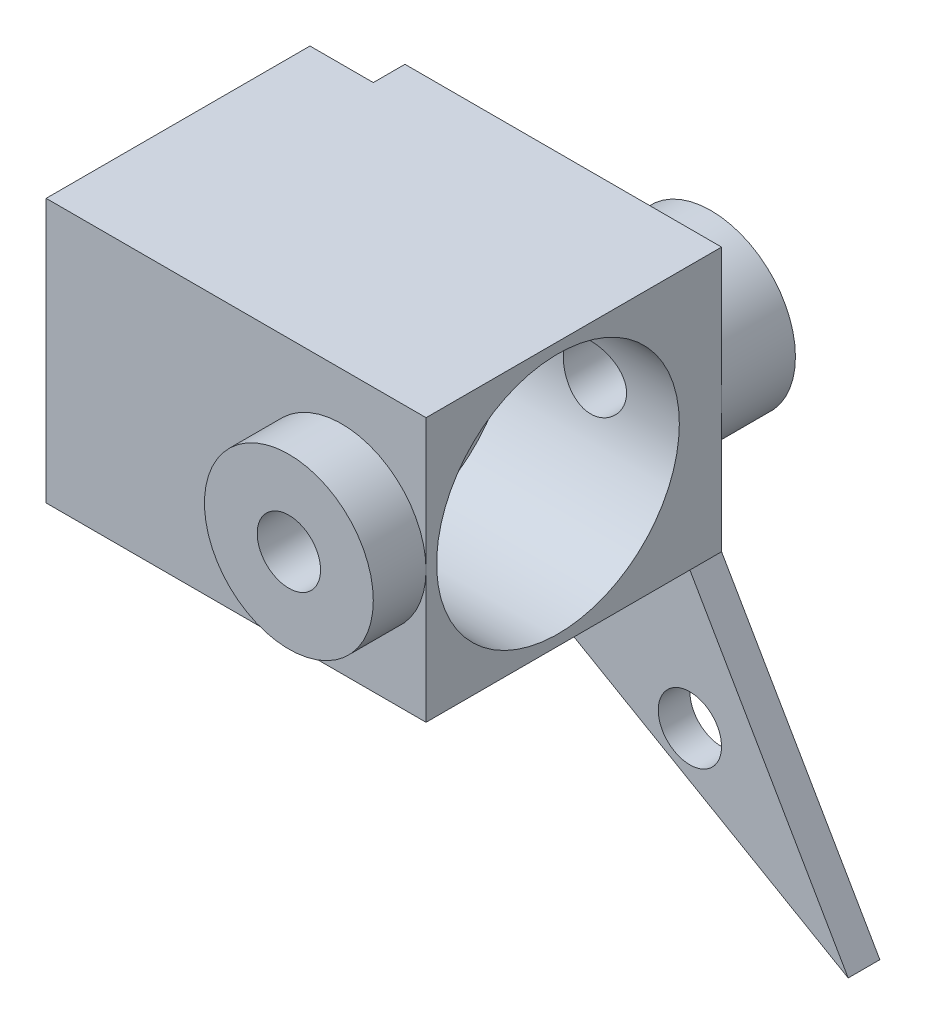
SolidWorks part; units mm, degrees
ref_plane "前视基准面" through (0, 0, 0) normal (0, 0, 1) x (1, 0, 0)
ref_plane "上视基准面" through (0, 0, 0) normal (0, 1, 0) x (1, 0, 0)
ref_plane "右视基准面" through (0, 0, 0) normal (1, 0, 0) x (0, 0, -1)
other "Configuration Table"
sketch "草图1" plane through (0, 0, 0) normal (0, 0, 1) x (1, 0, 0)
  line L0 (-52.6872, 0) -> (52.6872, 0) construction
  line L1 (0, -45.2005) -> (0, 45.2005) construction
  line L3 (-17.5, 12.5) -> (17.5, 12.5)
  line L4 (-17.5, 12.5) -> (-17.5, -12.5)
  line L5 (-17.5, -12.5) -> (17.5, -12.5)
  line L6 (17.5, 12.5) -> (17.5, -12.5)
  circle A0 centre (9.5, 0) radius 8
  point P4 (0, 0)
  point P8 (0, 0)
  dimension "D1" = 35
  dimension "D2" = 25
extrude "凸台-拉伸2" add sketch "草图1" along normal blind 25 contours L6 A0 L3 L4 L5 | A0
sketch "草图2" plane through (0, 0, 25) normal (0, 0, 1) x (1, 0, 0)
  line L0 (0, 0) -> (50000, 0) construction
  line L1 (0, 0) -> (0, 50000) construction
  line L2 (17.5, 12.5) -> (17.5, -12.5) construction
  circle A0 centre (9.5, 0) radius 8
extrude "凸台-拉伸3" add sketch "草图2" along normal blind 5 contours A0
sketch "草图3" plane through (0, 0, 0) normal (0, 0, -1) x (-1, 0, 0)
  line L0 (-17.5, 0) -> (49982.5, 0) construction
  line L1 (0, 0) -> (0, 50000) construction
  line L2 (-17.5, 12.5) -> (-17.5, -12.5) construction
  circle A0 centre (-9.5, 0) radius 8
extrude "凸台-拉伸4" add sketch "草图3" along normal blind 10
sketch "草图4" plane through (0, 0, 30) normal (0, 0, 1) x (1, 0, 0)
  circle A0 centre (9.5, 0) radius 3
extrude "切除-拉伸1" cut sketch "草图4" against normal through all contours A0
sketch "草图5" plane through (17.5, 0, 0) normal (1, 0, 0) x (0, 0, -1)
  line L0 (-12.5, 40.5372) -> (-12.5, -15.5372) construction
  line L2 (-25, 0) -> (49975, 0) construction
  circle A0 centre (-12.5, 0) radius 11.5
  point P3 (-12.5, 12.5)
extrude "切除-拉伸2" cut sketch "草图5" against normal blind 16
sketch "草图6" plane through (-17.5, 0, 0) normal (-1, 0, 0) x (0, 0, 1)
  line L0 (0, 0) -> (50000, 0) construction
  line L1 (12.5, 12.5) -> (12.5, 50012.5) construction
  line L2 (25, 12.5) -> (0, 12.5) construction
  circle A0 centre (12.5, 0) radius 4
  point P7 (12.5, 12.5)
extrude "凸台-拉伸5" add sketch "草图6" along normal blind 15
sketch "草图8" plane through (-17.5, 0, 0) normal (-1, 0, 0) x (0, 0, 1)
  line L0 (0, 0) -> (50000, 0) construction
  line L1 (12.5, 0) -> (12.5, 50000) construction
  line L3 (18.5, -1.0127) -> (15.5, -1.0127)
  line L4 (18.5, -1.0127) -> (18.5, 1.0127)
  line L5 (18.5, 1.0127) -> (15.5, 1.0127)
  line L6 (15.5, -1.0127) -> (15.5, 1.0127)
  dimension "D1" = 3
  dimension "D2" = 3
extrude "切除-拉伸3" cut sketch "草图8" along normal blind 15 contours L4 L3 L6 L5
sketch "草图9" plane through (-32.5, 0, 0) normal (-1, 0, 0) x (0, 0, 1)
  circle A0 centre (12.5, 0) radius 4
extrude "凸台-拉伸6" add sketch "草图9" against normal blind 2
sketch "草图10" plane through (-17.5, 0, 0) normal (-1, 0, 0) x (0, 0, 1)
  circle A0 centre (12.5, 0) radius 4
extrude "凸台-拉伸7" add sketch "草图10" along normal blind 2
sketch "草图12" plane through (0, 0, 0) normal (0, 0, -1) x (-1, 0, 0)
  line L0 (-17.5, -12.5) -> (12.5, -12.5)
  line L1 (17.5, -12.5) -> (-17.5, -12.5) construction
  line L4 (12.5, -12.5) -> (-32.5, -38.4808)
  line L5 (-32.5, -38.4808) -> (-2.5, -12.5)
  line L6 (-17.5, -12.5) -> (-32.5, -38.4808)
  line L7 (-17.5, -12.5) -> (-17.5, -25.4904)
  line L8 (12.5, -12.5) -> (12.5, 12.5)
  line L9 (17.5, 12.5) -> (-17.5, 12.5) construction
  line L10 (12.5, 12.5) -> (-17.5, 12.5)
  line L11 (-17.5, 12.5) -> (-17.5, -12.5)
  line L13 (-17.5, -12.5) -> (-24.1279, -12.5)
  line L14 (-17.5, -12.5) -> (-17.5, 12.5)
  line L15 (-17.5, 12.5) -> (-24.1279, 12.5)
  line L16 (-24.1279, -12.5) -> (-24.1279, 12.5)
  circle A1 centre (-17.5, -25.4904) radius 3
  circle A2 centre (-9.5, 0) radius 8
  line M7 (-17.5, 12.5) -> (-17.5, 0)
  circle M8 centre (-9.5, 0) radius 8
  line M9 (-17.5, 0) -> (-17.5, -12.5)
  line M10 (-17.5, -12.5) -> (17.5, -12.5)
  line M12 (17.5, 12.5) -> (-17.5, 12.5)
  dimension "D1" = 30
  dimension "D2" = 120
extrude "凸台-拉伸11" add sketch "草图12" along normal blind 3 contours L0 L8 M12 M7 M8 M9 M10 | L16 L13 L15 M9 M7 | A1 L5 L7 M10 | A1 L7 L6 L5 | A1 L5 L4 L0
sketch "草图14" plane through (0, 0, 0) normal (0, 0, 1) x (1, 0, 0)
  line L0 (24.1279, -12.5) -> (24.1279, 12.5) construction
  line L1 (17.5, 12.5) -> (24.1279, 12.5)
  line L2 (17.5, 12.5) -> (17.5, -12.5)
  line L3 (17.5, -12.5) -> (24.1279, -12.5)
  line L4 (24.1279, 12.5) -> (24.1279, -12.5)
extrude "切除-拉伸4" cut sketch "草图14" against normal blind 3 contours L2 L1 L4 L3
sketch "草图15" plane through (-17.5, 0, 0) normal (-1, 0, 0) x (0, 0, 1)
  line L1 (0, 12.5) -> (25, 12.5)
  line L2 (0, 12.5) -> (0, -12.5)
  line L3 (0, -12.5) -> (25, -12.5)
  line L4 (25, 12.5) -> (25, -12.5)
extrude "切除-拉伸5" cut sketch "草图15" along normal through all
sketch "草图16" plane through (-17.5, 0, 0) normal (-1, 0, 0) x (0, 0, 1)
  line L0 (-36.9342, 0) -> (36.9342, 0) construction
  line L2 (12.5, 12.5) -> (12.5, 50012.5) construction
  line L3 (25, 12.5) -> (0, 12.5) construction
  line L4 (0, -27.5) -> (0, 27.5) construction
  line L5 (25, -12.5) -> (0, -12.5)
  line L6 (25, -12.5) -> (25, 12.5)
  line L7 (25, 12.5) -> (0, 12.5)
  line L8 (0, -12.5) -> (0, 12.5)
  circle A0 centre (12.5, 0) radius 4
  point P4 (0, 0)
  point P9 (12.5, 12.5)
extrude "凸台-拉伸12" add sketch "草图16" along normal blind 1
